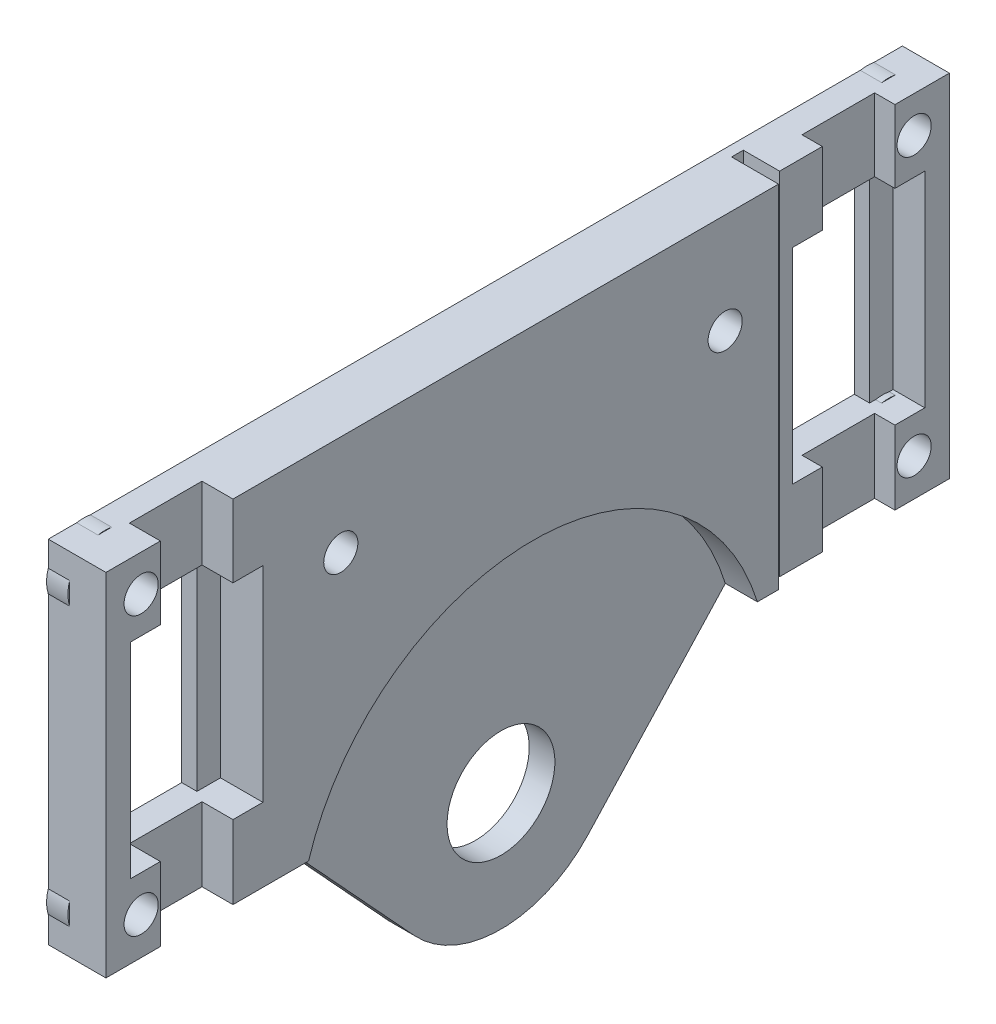
SolidWorks part; units mm, degrees
ref_plane "Face" through (0, 0, 0) normal (0, 0, 1) x (1, 0, 0)
ref_plane "Dessus" through (0, 0, 0) normal (0, 1, 0) x (1, 0, 0)
ref_plane "Droite" through (0, 0, 0) normal (1, 0, 0) x (0, 0, -1)
sketch "Esquisse2" plane through (0, 0, 0) normal (1, 0, 0) x (0, 0, -1)
  line L0 (-40, -15) -> (40, -15)
  line L4 (-40, -15) -> (-40, 70)
  line L8 (-40, 70) -> (40, 70)
  line L9 (40, 70) -> (40, -15)
  dimension "D1" = 70
  dimension "D2" = 15
  dimension "D3" = 40
  dimension "D4" = 40
extrude "plaque" add sketch "Esquisse2" along normal blind 5.4
ref_plane "Plan_posic" through (2.4, 0, 0) normal (-1, 0, 0) x (0, 0, 1)
sketch "Esquisse13" plane through (0, 0, 0) normal (1, 0, 0) x (0, 0, -1)
  line L0 (-7, 20) -> (-7, 0)
  line L1 (-7, 20) -> (7, 20)
  line L2 (-7, 0) -> (7, 0)
  line L3 (7, 20) -> (7, 0)
  line L4 (-7, 20) -> (7, 0) construction
  line L5 (-7, 0) -> (7, 20) construction
  line L6 (0, 10) -> (0, 0) construction
  line L7 (0, 0) -> (0, -16.5568) construction
  point P1 (0, 10)
  dimension "D1" = 20
  dimension "D2" = 14
  dimension "D3" = 180
  dimension "D4" = 20
extrude "extension plaque pour posic" [suppressed] add sketch "Esquisse13" along normal up to surface (5.8 mm away)
sketch "Esquisse14" plane through (0, 0, 0) normal (1, 0, 0) x (0, 0, -1)
  circle A0 centre (0, -12) radius 5.05
  dimension "D1" = 10.1
  dimension "D2" = 12
sketch "Esquisse15" plane through (2.4, 0, 0) normal (-1, 0, 0) x (0, 0, 1)
  circle A0 centre (0, -12) radius 22
  dimension "D1" = 12
  dimension "D2" = 44
extrude "dégagement roue" cut sketch "Esquisse15" against normal through all
sketch "Esquisse18" plane through (0, 0, 0) normal (1, 0, 0) x (0, 0, -1)
  line L0 (-5.7851, -6.8944) -> (-7.4469, -5.5) construction
  line L1 (-7.4469, -5.5) -> (-40, -5.5)
  line L2 (-40, -5.5) -> (-40, -15)
  line L3 (-7.4469, -5.5) -> (7.4469, -5.5)
  line L4 (0, -5.5) -> (0, 0) construction
  line L5 (5.7851, -6.8944) -> (7.4469, -5.5) construction
  line L6 (7.4469, -5.5) -> (40, -5.5)
  line L7 (40, -5.5) -> (40, -15)
  line L8 (40, -15) -> (-40, -15)
  arc A0 (5.7851, -6.8944) -> (-5.7851, -6.8944) centre (0, 0) cw construction
  dimension "D1" = 5.5
  dimension "D2" = 9
  dimension "D3" = 50
extrude "découpe_inférieure" cut sketch "Esquisse18" along normal through all
extrude "renfort_roulement" add sketch "Esquisse14" along normal up to surface (2.4 mm away) thin
sketch "Esquisse20" plane through (0, 0, 0) normal (1, 0, 0) x (0, 0, -1)
  line L0 (-40, 70) -> (40, 70)
  line L1 (40, 70) -> (40, 62.5)
  line L2 (40, 62.5) -> (26, 62.5)
  line L3 (21.1704, 58.7941) -> (15.5592, 37.853)
  line L4 (13.1444, 36) -> (-13.1444, 36)
  line L5 (-15.5592, 37.853) -> (-21.1704, 58.7941)
  line L6 (-26, 62.5) -> (-40, 62.5)
  line L7 (-40, 62.5) -> (-40, 70)
  line L8 (0, 0) -> (0, 36) construction
  line L9 (0, 70) -> (0, 36) construction
  arc A0 (26, 62.5) -> (21.1704, 58.7941) centre (26, 57.5) ccw
  arc A1 (15.5592, 37.853) -> (13.1444, 36) centre (13.1444, 38.5) cw
  arc A2 (-13.1444, 36) -> (-15.5592, 37.853) centre (-13.1444, 38.5) cw
  arc A3 (-21.1704, 58.7941) -> (-26, 62.5) centre (-26, 57.5) ccw
  dimension "D1" = 7.5
  dimension "D3" = 2.5
  dimension "D4" = 5
  dimension "D2" = 36
  dimension "D5" = 15
  dimension "D6" = 26
extrude "découpe_supérieure" cut sketch "Esquisse20" along normal through all
sketch "Esquisse26" plane through (0, 0, 0) normal (0, 1, 0) x (1, 0, 0)
  line L0 (5.9, 31.5) -> (5.9, -31.5) construction
  line L1 (0, 0) -> (5.9, 0) construction
  line L3 (2.5, 28.1) -> (9.3, 28.1)
  line L4 (2.5, 28.1) -> (2.5, 34.9)
  line L5 (2.5, 34.9) -> (9.3, 34.9)
  line L6 (9.3, 28.1) -> (9.3, 34.9)
  line L7 (2.5, 28.1) -> (9.3, 34.9) construction
  line L8 (2.5, 34.9) -> (9.3, 28.1) construction
  line L9 (2.5, -34.9) -> (9.3, -34.9)
  line L10 (2.5, -34.9) -> (2.5, -28.1)
  line L11 (2.5, -28.1) -> (9.3, -28.1)
  line L12 (9.3, -34.9) -> (9.3, -28.1)
  line L13 (2.5, -34.9) -> (9.3, -28.1) construction
  line L14 (2.5, -28.1) -> (9.3, -34.9) construction
  dimension "D1" = 5.9
  dimension "D2" = 63
  dimension "D3" = 6.8
extrude "dégagement axe 6" cut sketch "Esquisse26" against normal through all and the other way through all
sketch "Esquisse28" plane through (0, 0, 0) normal (0, 1, 0) x (1, 0, 0)
  line L1 (0, 35.5) -> (1.4279, 35.5)
  line L2 (0, 35.5) -> (0, 27.5)
  line L3 (0, 27.5) -> (1.4279, 27.5)
  line L4 (1.4279, 35.5) -> (1.4279, 27.5) construction
  line L5 (5.9, 31.5) -> (1.4279, 31.5) construction
  line L6 (1.4279, 35.5) -> (1.4279, 37.7)
  line L7 (10.3721, 25.3) -> (1.4279, 25.3)
  line L8 (10.3721, 25.3) -> (10.3721, 37.7)
  line L9 (10.3721, 37.7) -> (1.4279, 37.7)
  line L10 (1.4279, 25.3) -> (1.4279, 27.5)
  line L11 (10.3721, 25.3) -> (1.4279, 37.7) construction
  line L12 (10.3721, 37.7) -> (1.4279, 25.3) construction
  line L13 (0, 40) -> (0, 8.936) construction
  line L14 (10.3721, -25.3) -> (1.4279, -25.3)
  line L15 (10.3721, -25.3) -> (10.3721, -37.7)
  line L16 (10.3721, -37.7) -> (1.4279, -37.7)
  line L17 (1.4279, -25.3) -> (1.4279, -27.5)
  line L18 (10.3721, -25.3) -> (1.4279, -37.7) construction
  line L19 (10.3721, -37.7) -> (1.4279, -25.3) construction
  line L20 (1.4279, -31.5) -> (5.9, -31.5) construction
  line L21 (0, -27.5) -> (1.4279, -27.5)
  line L22 (0, -27.5) -> (0, -35.5)
  line L23 (0, -35.5) -> (1.4279, -35.5)
  line L24 (1.4279, -27.5) -> (1.4279, -35.5) construction
  line L25 (1.4279, -35.5) -> (1.4279, -37.7)
  circle A0 centre (5.9, 31.5) radius 6 construction
  circle A1 centre (5.9, -31.5) radius 6 construction
  dimension "D1" = 12
  dimension "D2" = 8
  dimension "D3" = 6.2
extrude "dégagement douille" cut sketch "Esquisse28" along normal blind 19.2 from offset 1.4
sketch "Esquisse29" plane through (5.4, 0, 0) normal (1, 0, 0) x (0, 0, -1)
  line L0 (26.0071, 19.8929) -> (25.2293, 20.6707) construction
  line L1 (36.2858, 20.6) -> (37.7, 19.1858) construction
  line L2 (26.7142, 20.6) -> (25.3, 19.1858) construction
  line L3 (28.1, 20.6) -> (25.3, 20.6) construction
  line L4 (25.3, 1.4) -> (25.3, 20.6) construction
  line L5 (37.7, 20.6) -> (35.5, 20.6) construction
  line L6 (26.7142, 20.6) -> (36.2858, 20.6)
  line L7 (37.7, 20.6) -> (37.7, 1.4) construction
  line L8 (36.9929, 19.8929) -> (37.7707, 20.6707) construction
  line L9 (26.9294, 18.6) -> (36.0706, 18.6)
  arc A0 (25.3, 19.1858) -> (26.7142, 20.6) centre (25.9396, 19.9604) cw
  arc A1 (36.2858, 20.6) -> (37.7, 19.1858) centre (37.0604, 19.9604) cw
  arc A2 (25.3, 19.1858) -> (26.9294, 18.6) centre (26.9294, 21.1591) ccw
  arc A3 (36.0706, 18.6) -> (37.7, 19.1858) centre (36.0706, 21.1591) ccw
  dimension "D1" = 45
  dimension "D3" = 1.1
  dimension "D4" = 2
  dimension "D2" = 2
extrude "degagement angle" [suppressed] cut sketch "Esquisse29" against normal through all
ref_plane "Plan1" through (0, 11, 0) normal (0, 1, 0) x (1, 0, 0)
mirror "Symétrie2" [suppressed] about plane through (0, 11, 0) normal (0, 1, 0)
mirror "Symétrie3" [suppressed] about plane through (0, 0, 0) normal (0, 0, 1)
pattern_linear "Répétition linéaire1" count 2 spacing 26 along (0, 1, 0) of "dégagement douille", "degagement angle", "Symétrie2", "Symétrie3"
sketch "Esquisse19" plane through (0, 0, 0) normal (0, 1, 0) x (1, 0, 0)
  line L0 (5.4, 40) -> (4.4, 40)
  line L1 (4.4, 40) -> (4.4, 24.1)
  line L2 (4.4, 24.1) -> (1, 24.1)
  line L3 (1, 24.1) -> (1, 23)
  line L4 (1, 23) -> (5.4, 23)
  line L5 (5.4, 23) -> (5.4, 40)
  dimension "D1" = 23
  dimension "D2" = 1.1
  dimension "D3" = 1
  dimension "D4" = 1
extrude "Mors_déformable_douille" cut sketch "Esquisse19" against normal through all and the other way through all
sketch "position perçage" plane through (0, 0, 0) normal (1, 0, 0) x (0, 0, -1)
  line L0 (-18, 18) -> (18, 18) construction
  line L1 (0, 18) -> (0, 0) construction
  line L2 (-36.7, 24) -> (-36.7, -2) construction
  line L3 (36.7, 24) -> (-36.7, 24) construction
  line L4 (36.7, -2) -> (36.7, 24) construction
  line L5 (0, 18) -> (0, 24) construction
  line L6 (0, 24) -> (0, 34) construction
  line L7 (-34.9, -5.5) -> (-40, -5.5) construction
  line L9 (-40, 62.5) -> (-40, -5.5) construction
  line L10 (-21, 34) -> (21, 34) construction
  dimension "D1" = 36
  dimension "D2" = 18
  dimension "D3" = 3.3
  dimension "D4" = 3.5
  dimension "D5" = 26
  dimension "D6" = 42
  dimension "D7" = 10
hole_wizard "Fraisage pour vis à tête fraisée bombée fendue M31" positions "Esquisse23" profile "Esquisse22" countersink size "M3" standard "Ansi Metric" end condition through all
sketch "Esquisse23" plane through (0, 0, 0) normal (-1, 0, 0) x (0, 0, 1)
  point P0 (18, 18)
  point P4 (36.7, 24)
  point P7 (36.7, -2)
  point P10 (21, 34)
sketch "Esquisse22" plane through (0, 18, 18) normal (0, 1, 0) x (0, 0, 1)
  line L0 (0, 0) -> (0, 5.4)
  line L1 (0, 5.4) -> (1.6, 5.4)
  line L2 (1.6, 5.4) -> (1.6, 1.86)
  line L3 (1.6, 1.86) -> (3.46, 0)
  line L5 (3.46, 0) -> (0, 0)
  line L6 (-1.6, 1.86) -> (-3.46, 0) construction
  line L11 (0, -6.35) -> (0, 107.95) construction
  dimension "Diamètre du perçage jusqu'au prochain" = 3.2
  dimension "Profondeur du perçage jusqu'au prochain" = 5.4
  dimension "Diamètre du fraisage entrant" = 6.92
  dimension "Angle du fraisage entrant" = 90
sketch "Esquisse31" plane through (5.4, 0, 0) normal (1, 0, 0) x (0, 0, -1)
  line L0 (40, -5.5) -> (40, 62.5) construction
  line L1 (-40, 62.5) -> (40, 62.5)
  line L2 (-40, 62.5) -> (-40, 27.4)
  line L3 (-40, 27.4) -> (40, 27.4)
  line L4 (40, 62.5) -> (40, 27.4)
  line L5 (37.7, 27.4) -> (34.9, 27.4) construction
extrude "Enlèv. mat.-Extru.1" cut sketch "Esquisse31" against normal up to surface (5.4 mm away) up to face at (0, 18, 21.46)
sketch "Esquisse33" plane through (2.4, 0, 0) normal (1, 0, 0) x (0, 0, -1)
  line L0 (-8.1254, -19.4887) -> (-21.0178, -5.5)
  line L1 (0, 0) -> (0, -12) construction
  line L2 (-21.0178, -5.5) -> (-8.936, -5.5)
  line L3 (-8.936, -5.5) -> (-8.1254, -19.4887)
  line L4 (8.1254, -19.4887) -> (21.0178, -5.5)
  line L5 (8.1254, -19.4887) -> (8.936, -5.5)
  line L6 (8.936, -5.5) -> (21.0178, -5.5)
  arc A1 (-8.936, -5.5) -> (8.936, -5.5) centre (0, -12) ccw construction
extrude "Boss.-Extru.1" add sketch "Esquisse33" against normal up to surface (2.4 mm away) up to face at (0, 26.7358, 39.2226)
mirror "Symétrie4" about plane through (0, 0, 0) normal (0, 0, 1) of "Fraisage pour vis à tête fraisée bombée fendue M31"
sketch "Esquisse34" plane through (0, 0, 0) normal (-1, 0, 0) x (0, 0, 1)
  line L0 (0, 27.4) -> (0, -28.1104) construction
  line L1 (-36.0584, 27.4) -> (36.0584, 27.4) construction
  circle A0 centre (-36.7, 24) radius 3.46
  circle A1 centre (-36.7, -2) radius 3.46
  circle A2 centre (-36.7, 24) radius 1.6
  circle A3 centre (-36.7, 24) radius 1.6 construction
  circle A4 centre (-36.7, -2) radius 1.6
  circle A5 centre (-36.7, -2) radius 1.6 construction
  circle A6 centre (-18, 18) radius 3.46
  arc A7 (-40, 22.96) -> (-36.0584, 27.4) centre (-36.7, 24) ccw construction
  arc A8 (-40, -3.04) -> (-40, -0.96) centre (-36.7, -2) ccw construction
  circle A9 centre (-18, 18) radius 3.46 construction
  circle A10 centre (-18, 18) radius 1.6
  circle A11 centre (-18, 18) radius 1.6 construction
  circle A12 centre (18, 18) radius 1.6
  circle A13 centre (18, 18) radius 3.46
  circle A14 centre (36.7, -2) radius 1.6
  circle A15 centre (36.7, 24) radius 1.6
  circle A16 centre (36.7, -2) radius 3.46
  circle A17 centre (36.7, 24) radius 3.46
extrude "Boss.-Extru.3" add sketch "Esquisse34" against normal blind 2
